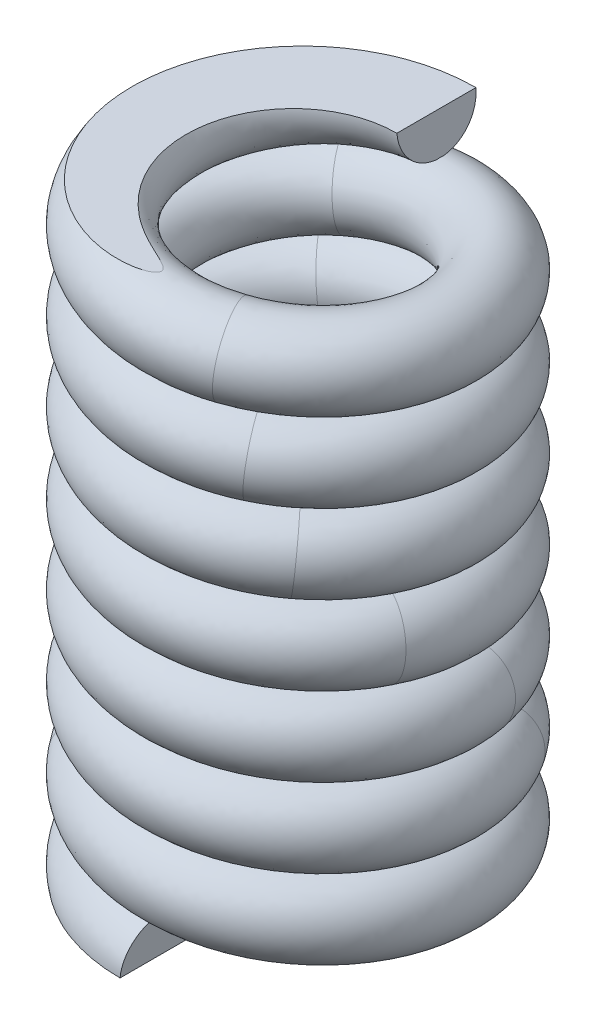
SolidWorks part; units mm, degrees
ref_plane "Ön Düzlem" through (0, 0, 0) normal (0, 0, 1) x (1, 0, 0)
ref_plane "Üst Düzlem" through (0, 0, 0) normal (0, 1, 0) x (1, 0, 0)
ref_plane "Sağ Düzlem" through (0, 0, 0) normal (1, 0, 0) x (0, 0, -1)
sketch "Çizim3" plane through (0, 0, 0) normal (0, 1, 0) x (1, 0, 0)
  circle A0 centre (0, 0) radius 3.5
curve "Helis/Spiral1" pitch 2 height 15 turns 7.5
sweep "Süpür1" add path "Helis/Spiral1" circular profile diameter 2 parameters "D3"=2
sketch "Çizim10" plane through (0, 0, 0) normal (0, 1, 0) x (1, 0, 0)
  circle A0 centre (0, 0) radius 5
extrude "Kes-Ekstrüzyon1" cut sketch "Çizim10" against normal blind 10
ref_plane "Düzlem1" through (0, 15, 0) normal (0, -1, 0) x (-1, 0, 0)
sketch "Çizim11" plane through (0, 15, 0) normal (0, -1, 0) x (-1, 0, 0)
  circle A1 centre (0, 0) radius 5
  circle A2 centre (0, 0) radius 5
  dimension "D1" = 0
extrude "Kes-Ekstrüzyon2" cut sketch "Çizim11" against normal blind 10
